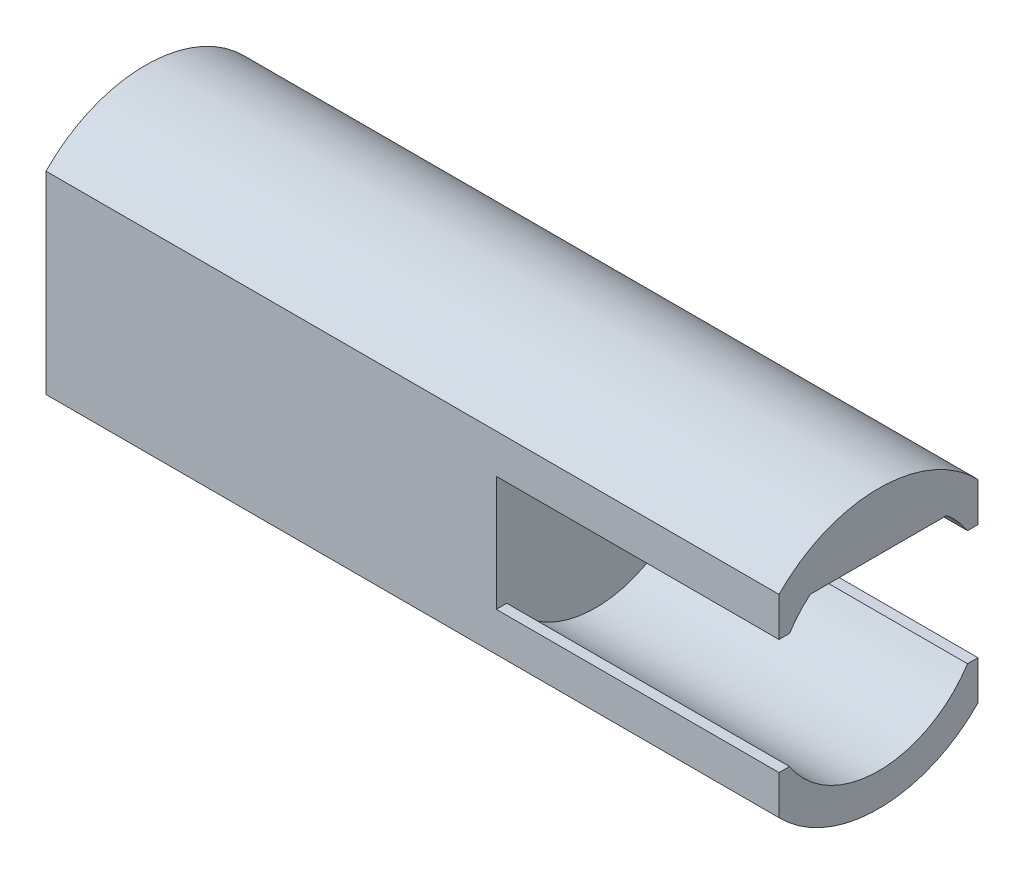
SolidWorks part; units mm, degrees
ref_plane "Front Plane" through (0, 0, 0) normal (0, 0, 1) x (1, 0, 0)
ref_plane "Top Plane" through (0, 0, 0) normal (0, 1, 0) x (1, 0, 0)
ref_plane "Right Plane" through (0, 0, 0) normal (1, 0, 0) x (0, 0, -1)
sketch "Sketch1" plane through (0, 0, 0) normal (1, 0, 0) x (0, 0, -1)
  line L0 (-1.9, 1.8473) -> (-1.9, -1.8473)
  line L1 (1.9, 1.8473) -> (1.9, -1.8473)
  line L2 (-1.3031, 1.55) -> (1.3031, 1.55)
  arc A0 (-1.9, -1.8473) -> (1.9, -1.8473) centre (0, 0) ccw
  arc A2 (1.9, 1.8473) -> (-1.9, 1.8473) centre (0, 0) ccw
  arc A3 (-1.3031, 1.55) -> (1.3031, 1.55) centre (0, 0) ccw
  point P9 (0, -2.025)
  dimension "D3" = 5.3
  dimension "D4" = 4.05
  dimension "D1" = 3.8
  dimension "D2" = 1.9
  dimension "D5" = 1.55
sketch "Sketch2" plane through (0, 0, 0) normal (1, 0, 0) x (0, 0, -1)
  line L0 (-1.9, -1.8473) -> (-1.9, -1.1003)
  line L2 (-1.9, 1.8473) -> (-1.9, 1.1003)
  line L3 (1.9, 1.8473) -> (1.9, 1.1003)
  line L5 (1.9, -1.8473) -> (1.9, -1.1003)
  line L6 (-1.9, 1.1003) -> (-1.7, 1.1003)
  line L7 (1.7, 1.1003) -> (1.9, 1.1003)
  line L8 (-1.9, -1.1003) -> (-1.7, -1.1003)
  line L9 (1.7, -1.1003) -> (1.9, -1.1003)
  line L10 (-1.3031, 1.55) -> (1.3031, 1.55)
  arc A0 (-1.9, 1.8473) -> (1.9, 1.8473) centre (0, 0) cw
  arc A1 (1.9, 1.8473) -> (-1.9, 1.8473) centre (0, 0) ccw construction
  arc A2 (-1.9, -1.8473) -> (1.9, -1.8473) centre (0, 0) ccw
  arc A3 (-1.9, -1.8473) -> (1.9, -1.8473) centre (0, 0) ccw construction
  arc A4 (-1.7, -1.1003) -> (1.7, -1.1003) centre (0, 0) ccw
  circle A5 centre (0, 0) radius 2.025 construction
  arc A6 (1.7, 1.1003) -> (1.3031, 1.55) centre (0, 0) ccw
  arc A7 (-1.3031, 1.55) -> (-1.7, 1.1003) centre (0, 0) ccw
  dimension "D1" = 0.2
  dimension "D2" = 0.2
extrude "Boss-Extrude1" add sketch "Sketch2" along normal blind 5.4
ref_plane "Plane1" through (-8.6, 0, 0) normal (1, 0, 0) x (0, 0, -1)
sketch "Sketch3" plane through (0, 0, 0) normal (-1, 0, 0) x (0, 0, 1)
  line L9 (1.9, -1.8473) -> (1.9, 1.8473)
  line L10 (-1.9, 1.8473) -> (-1.9, -1.8473)
  line L11 (1.9, -1.8473) -> (1.9, 1.8473)
  line L12 (-1.9, 1.8473) -> (-1.9, -1.8473)
  arc A8 (-1.9, -1.8473) -> (1.9, -1.8473) centre (0, 0) ccw
  arc A9 (1.9, 1.8473) -> (-1.9, 1.8473) centre (0, 0) ccw
  arc A10 (-1.9, -1.8473) -> (1.9, -1.8473) centre (0, 0) ccw
  arc A11 (1.9, 1.8473) -> (-1.9, 1.8473) centre (0, 0) ccw
  dimension "D1" = 0
extrude "Boss-Extrude2" add sketch "Sketch3" along direction (1, 0, 0) on the side of the normal up to surface (8.6 mm away) up to plane "Plane1"
equation "\"D2@Sketch1\"=\"D1@Sketch1\"/2"
